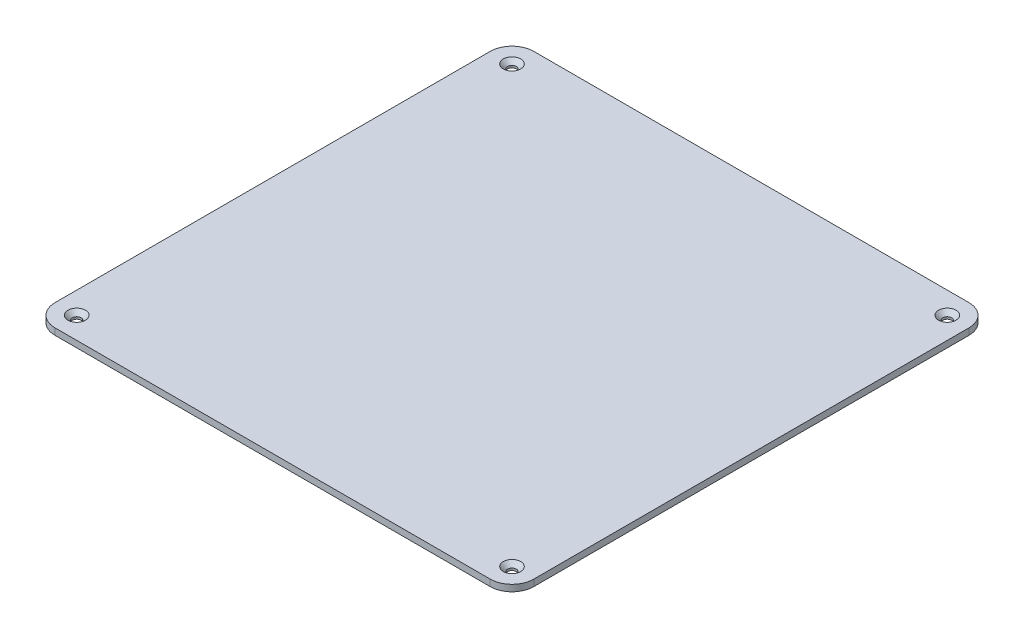
SolidWorks part; units mm, degrees
ref_plane "Front Plane" through (0, 0, 0) normal (0, 0, 1) x (1, 0, 0)
ref_plane "Top Plane" through (0, 0, 0) normal (0, 1, 0) x (1, 0, 0)
ref_plane "Right Plane" through (0, 0, 0) normal (1, 0, 0) x (0, 0, -1)
sketch "Sketch1" plane through (0, 0, 0) normal (0, 1, 0) x (1, 0, 0)
  line L1 (0, 0) -> (-220, 0)
  line L2 (0, 0) -> (0, 220)
  line L3 (0, 220) -> (-220, 220)
  line L4 (-220, 0) -> (-220, 220)
  point P4 (0, 0)
  dimension "D1" = 220
  dimension "D2" = 220
extrude "Boss-Extrude1" add sketch "Sketch1" along normal blind 3
fillet "Fillet1" radius 10 4 edges at (0, 1.5, -220) (0, 1.5, 0) (-220, 1.5, 0) (-220, 1.5, -220)
sketch "Sketch2" plane through (0, 3, 0) normal (0, 1, 0) x (1, 0, 0)
  line L0 (-110, 220) -> (-110, 0) construction
  line L1 (-10, 220) -> (-210, 220) construction
  line L2 (-210, 0) -> (-10, 0) construction
  circle A0 centre (-210, 210) radius 2
  circle A1 centre (-210, 10) radius 2
  circle A2 centre (-10, 10) radius 2
  circle A3 centre (-10, 210) radius 2
  dimension "D1" = 4
  dimension "D2" = 4
extrude "Cut-Extrude1" cut sketch "Sketch2" against normal blind 3
chamfer "Chamfer1" distance 2 angle 45 4 edges at (-210, 3, -8) (-10, 3, -12) (-10, 3, -212) (-210, 3, -208)
